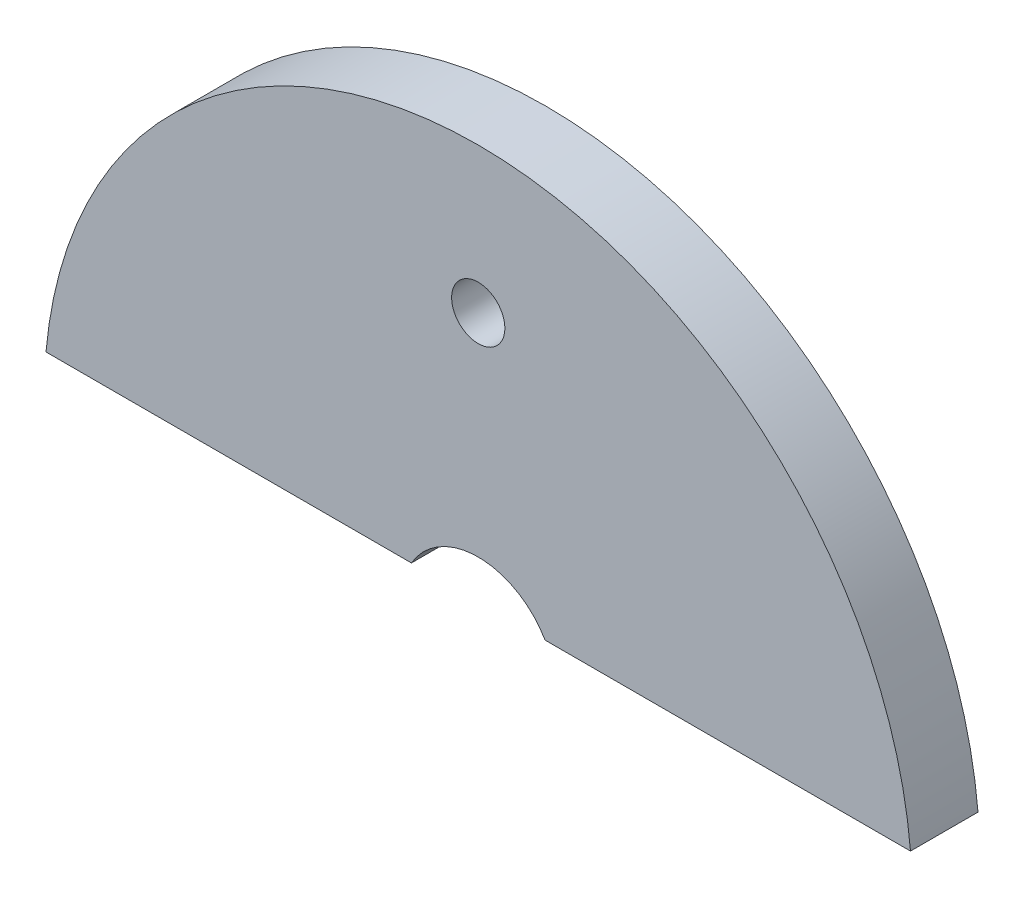
SolidWorks part; units mm, degrees
material "Cedar"
ref_plane "Front Plane" through (0, 0, 0) normal (0, 0, 1) x (1, 0, 0)
ref_plane "Top Plane" through (0, 0, 0) normal (0, 1, 0) x (1, 0, 0)
ref_plane "Right Plane" through (0, 0, 0) normal (1, 0, 0) x (0, 0, -1)
sketch "Sketch1" plane through (0, 0, 0) normal (0, 0, 1) x (1, 0, 0)
  line L0 (-28.4619, 2.54) -> (28.4619, 2.54)
  circle A0 centre (0, 0) radius 28.575
  circle A1 centre (0, 0) radius 5.08
  circle A2 centre (0, 18.9992) radius 1.7526
  dimension "D1" = 57.15
  dimension "D2" = 10.16
  dimension "D3" = 3.5052
  dimension "D4" = 18.9992
  dimension "D5" = 2.54
extrude "Boss-Extrude1" add sketch "Sketch1" along normal blind 4.445 contours A1 L0 A0 A2
